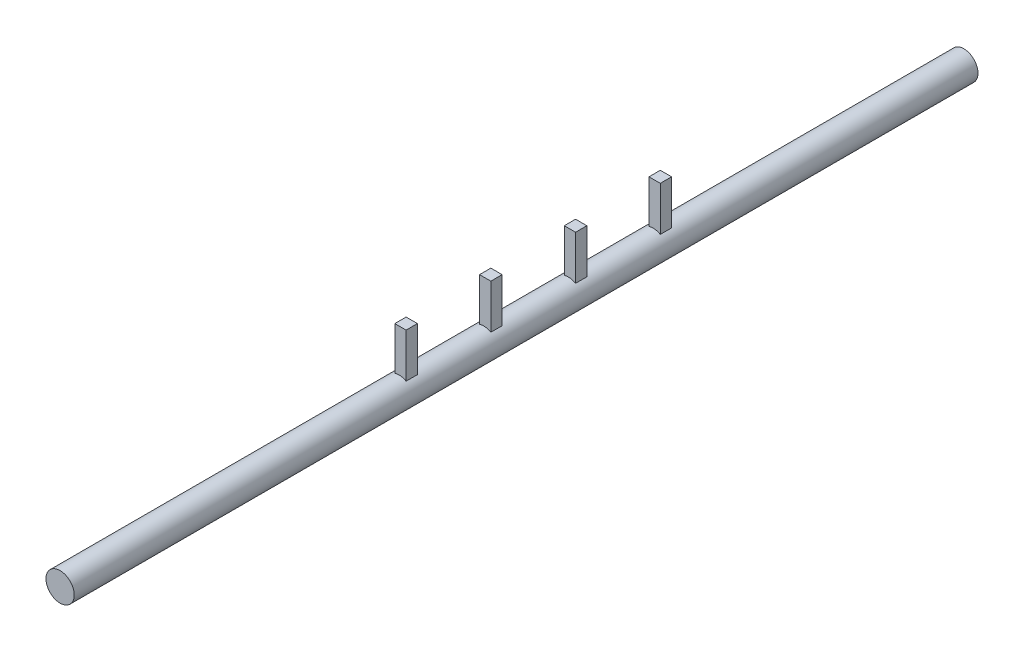
SolidWorks part; units mm, degrees
ref_plane "Front Plane" through (0, 0, 0) normal (0, 0, 1) x (1, 0, 0)
ref_plane "Top Plane" through (0, 0, 0) normal (0, 1, 0) x (1, 0, 0)
ref_plane "Right Plane" through (0, 0, 0) normal (1, 0, 0) x (0, 0, -1)
sketch "Sketch1" plane through (0, 0, 0) normal (0, 0, 1) x (1, 0, 0)
  circle A0 centre (0, 0) radius 3.175
  dimension "D1" = 6.35
extrude "Boss-Extrude1" add sketch "Sketch1" along normal blind 203.2
sketch "Sketch2" plane through (0, 0, 0) normal (0, 1, 0) x (1, 0, 0)
  line L0 (-0.9467, -107.95) -> (1.5933, -107.95)
  line L17 (-0.9467, -127) -> (1.5933, -127)
  line L18 (-0.9467, -127) -> (-0.9467, -124.46)
  line L19 (-0.9467, -124.46) -> (1.5933, -124.46)
  line L20 (1.5933, -127) -> (1.5933, -124.46)
  line L21 (-0.9467, -107.95) -> (-0.9467, -105.41)
  line L22 (1.5933, -107.95) -> (1.5933, -105.41)
  line L23 (-0.9467, -105.41) -> (1.5933, -105.41)
  line L24 (-0.9467, -88.9) -> (1.5933, -88.9)
  line L25 (-0.9467, -88.9) -> (-0.9467, -86.36)
  line L26 (1.5933, -88.9) -> (1.5933, -86.36)
  line L27 (-0.9467, -86.36) -> (1.5933, -86.36)
  line L28 (-0.9467, -69.85) -> (1.5933, -69.85)
  line L29 (-0.9467, -69.85) -> (-0.9467, -67.31)
  line L30 (1.5933, -69.85) -> (1.5933, -67.31)
  line L31 (-0.9467, -67.31) -> (1.5933, -67.31)
  line L32 (-3.175, -203.2) -> (3.175, -203.2) construction
  dimension "D1" = 2.54
  dimension "D2" = 4
  dimension "D3" = 76.2
extrude "Boss-Extrude2" add sketch "Sketch2" along normal blind 12.7
